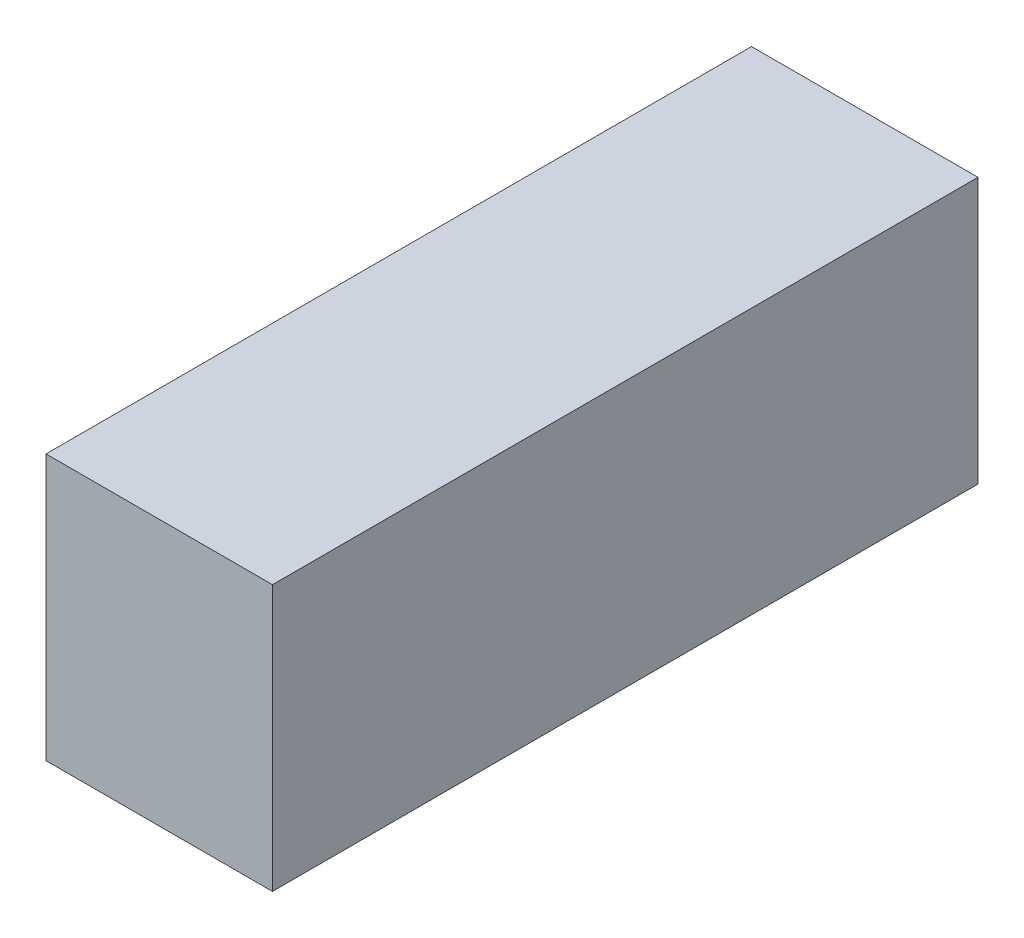
SolidWorks part; units mm, degrees
ref_plane "Front Plane" through (0, 0, 0) normal (0, 0, 1) x (1, 0, 0)
ref_plane "Top Plane" through (0, 0, 0) normal (0, 1, 0) x (1, 0, 0)
ref_plane "Right Plane" through (0, 0, 0) normal (1, 0, 0) x (0, 0, -1)
sketch "Sketch1" plane through (0, 0, 0) normal (0, 0, 1) x (1, 0, 0)
  line L1 (-26, 30.5) -> (26, 30.5)
  line L2 (-26, 30.5) -> (-26, -30.5)
  line L3 (-26, -30.5) -> (26, -30.5)
  line L4 (26, 30.5) -> (26, -30.5)
  line L5 (-26, 30.5) -> (26, -30.5) construction
  line L6 (-26, -30.5) -> (26, 30.5) construction
  point P0 (0, 0)
  dimension "D1" = 52
  dimension "D2" = 61
extrude "Boss-Extrude1" add sketch "Sketch1" along normal blind 162
